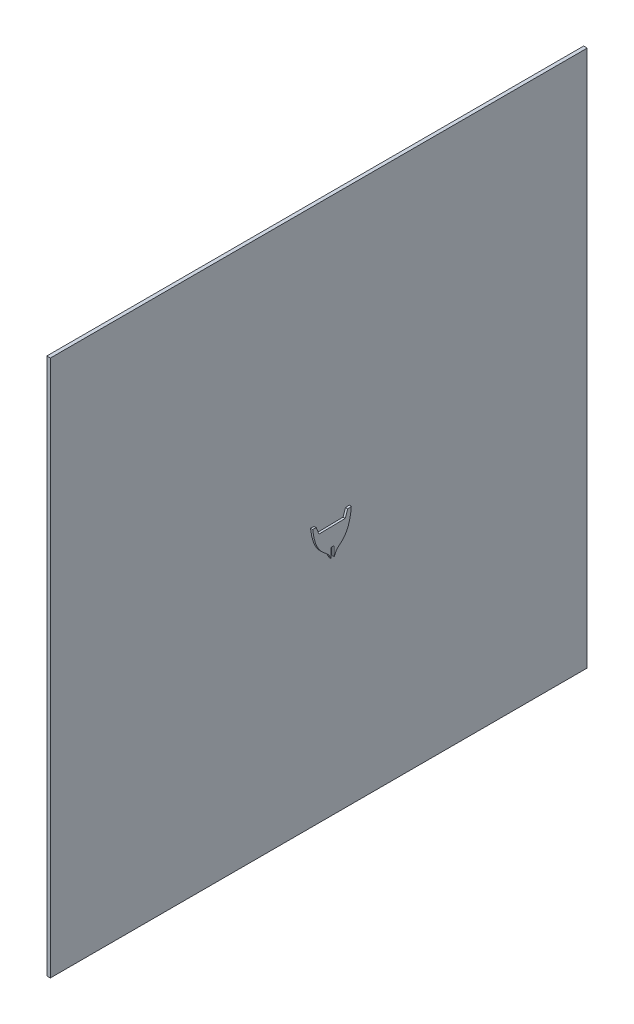
SolidWorks part; units mm, degrees
ref_plane "Plan de face" through (0, 0, 0) normal (0, 0, 1) x (1, 0, 0)
ref_plane "Plan de dessus" through (0, 0, 0) normal (0, 1, 0) x (1, 0, 0)
ref_plane "Plan de droite" through (0, 0, 0) normal (1, 0, 0) x (0, 0, -1)
sketch "Esquisse1" plane through (0, 0, 0) normal (0, 0, 1) x (1, 0, 0)
  point P0 (-20, 0)
  dimension "D1" = 20
sketch3d "Esquisse3D1"
  line L1 (-20, 1121.2893, 777.275) -> (-20, 1121.2893, -722.725)
  line L2 (-20, 1121.2893, 777.275) -> (-20, -378.7107, 777.275)
  line L3 (-20, -378.7107, 777.275) -> (-20, -378.7107, -722.725)
  line L4 (-20, 1121.2893, -722.725) -> (-20, -378.7107, -722.725)
  dimension "D1" = 1500
  dimension "D2" = 1500
extrude "Boss.-Extru.2" add sketch "Esquisse3D1" along direction (1, 0, 0) on the side of the normal blind 10 contours L2 L1 L4 L3
sketch "Esquisse4" plane through (-10, 0, 0) normal (1, 0, 0) x (0, 0, -1)
  line L0 (0, 0) -> (-7.701, 425.1082) construction
  line L1 (169.3944, 339.9131) -> (-188.5193, 333.4294) construction
  line L2 (-187.2006, 249.23) -> (169.0622, 255.6839) construction
  line L3 (-144.268, 175.2448) -> (126.4811, 180.1495) construction
sketch "Esquisse5" plane through (0, 0, 0) normal (1, 0, 0) x (0, 0, -1)
  line L0 (-7.701, 425.1082) -> (-4.4409, 245.146) construction
  line L1 (-42.7437, 336.0702) -> (30.5435, 337.3978)
  line L2 (-4.4409, 245.146) -> (5.2706, 286.9967) construction
  line L3 (5.2706, 286.9967) -> (14.3836, 279.4962) construction
  line L4 (14.3836, 279.4962) -> (42.3551, 288.3407) construction
  line L5 (42.3551, 288.3407) -> (47.5418, 358.0625) construction
  line L7 (0, 0) -> (-7.701, 425.1082) construction
  line L8 (47.5418, 358.0625) -> (37.3977, 357.038)
  line L9 (37.3977, 357.038) -> (30.5435, 337.3978)
  line L10 (169.3944, 339.9131) -> (-188.5193, 333.4294) construction
  line L16 (-144.268, 175.2448) -> (126.4811, 180.1495) construction
  line L18 (-4.4409, 245.146) -> (-15.6618, 286.6175) construction
  line L19 (-15.6618, 286.6175) -> (-24.4972, 278.7918) construction
  line L20 (-24.4972, 278.7918) -> (-52.7706, 286.6175) construction
  line L21 (-52.7706, 286.6175) -> (-60.4793, 356.1057) construction
  line L26 (-50.3047, 355.4493) -> (-42.7437, 336.0702)
  line L27 (-60.4793, 356.1057) -> (-50.3047, 355.4493)
  spline S0 degree 4 poles (-4.4409, 245.146) (5.2706, 286.9967) (14.3836, 279.4962) (42.3551, 288.3407) (47.5418, 358.0625) knots 0 0 0 0 0 1 1 1 1 1
  spline S1 degree 4 poles (-4.4409, 245.146) (-15.6618, 286.6175) (-24.4972, 278.7918) (-52.7706, 286.6175) (-60.4793, 356.1057) knots 0 0 0 0 0 1 1 1 1 1
  point P30 (-3.2209, 177.7999)
extrude "Boss.-Extru.3" add sketch "Esquisse5" along normal blind 6 separate body
sketch "Esquisse6" plane through (6, 0, 0) normal (1, 0, 0) x (0, 0, -1)
  line L0 (-9.2097, 259.9034) -> (-9.6988, 286.9034)
  line L1 (-9.6988, 286.9034) -> (-0.6988, 287.0665)
  line L2 (-0.6988, 287.0665) -> (-0.2097, 260.0665)
  line L3 (-0.2097, 260.0665) -> (117.0633, -47.527)
  line L4 (117.0633, -47.527) -> (-85.2277, -65.22)
  line L5 (-85.2277, -65.22) -> (-9.2097, 259.9034)
  line L6 (-9.2097, 259.9034) -> (-0.2097, 260.0665) construction
  line L7 (-144.268, 175.2448) -> (126.4811, 180.1495) construction
  spline S0 degree 4 poles (-60.4793, 356.1057) (-52.7706, 286.6175) (-24.4972, 278.7918) (-15.6618, 286.6175) (-4.4409, 245.146) knots 0 0 0 0 0 1 1 1 1 1 construction
  spline S1 degree 4 poles (-4.4409, 245.146) (5.2706, 286.9967) (14.3836, 279.4962) (42.3551, 288.3407) (47.5418, 358.0625) knots 0 0 0 0 0 1 1 1 1 1 construction
  dimension "D1" = 9
  dimension "D2" = 27
extrude "Enlèv. mat.-Extru.1" cut sketch "Esquisse6" against normal blind 6
